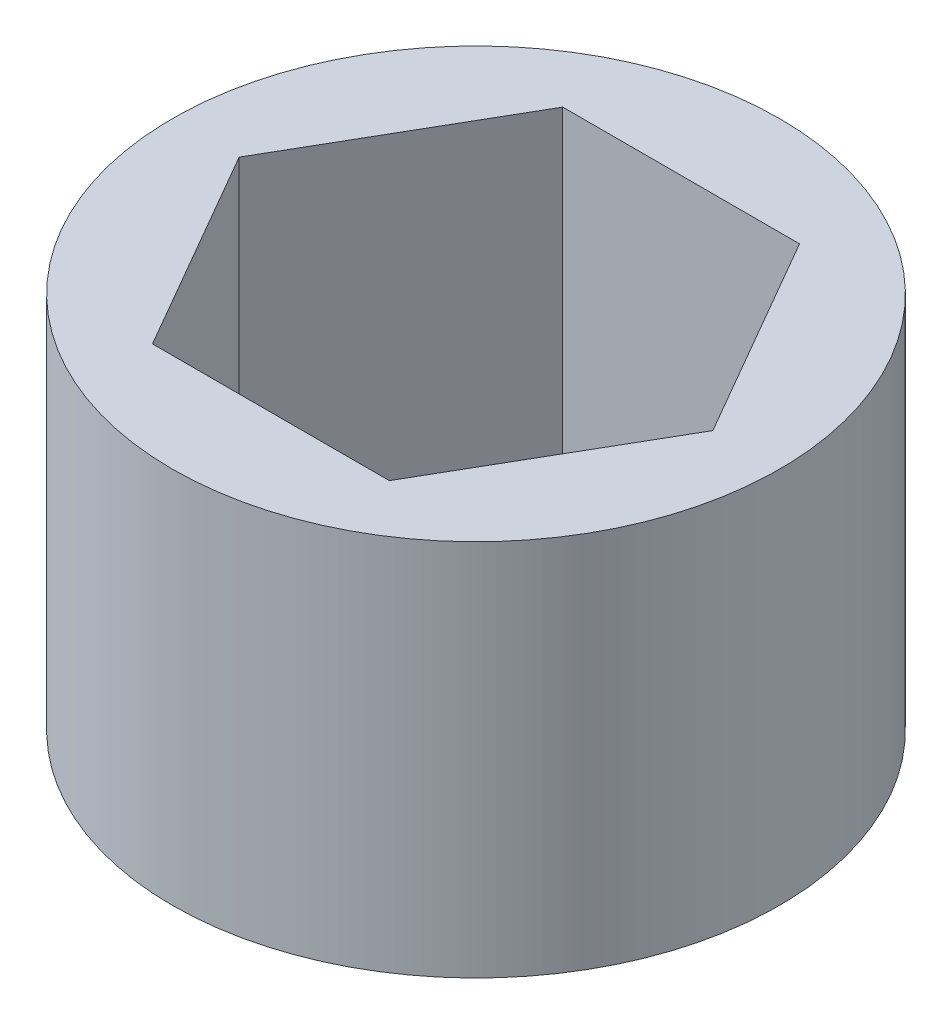
SolidWorks part; units mm, degrees
ref_plane "Front Plane" through (0, 0, 0) normal (0, 0, 1) x (1, 0, 0)
ref_plane "Top Plane" through (0, 0, 0) normal (0, 1, 0) x (1, 0, 0)
ref_plane "Right Plane" through (0, 0, 0) normal (1, 0, 0) x (0, 0, -1)
sketch "Sketch1" plane through (0, 0, 0) normal (0, 1, 0) x (1, 0, 0)
  line L1 (2.7863, -4.826) -> (5.5726, 0)
  line L2 (5.5726, 0) -> (2.7863, 4.826)
  line L3 (2.7863, 4.826) -> (-2.7863, 4.826)
  line L4 (-2.7863, 4.826) -> (-5.5726, 0)
  line L5 (-5.5726, 0) -> (-2.7863, -4.826)
  line L6 (-2.7863, -4.826) -> (2.7863, -4.826)
  circle A0 centre (0, 0) radius 7.1438
  circle A1 centre (0, 0) radius 4.826 construction
  dimension "D1" = 9.652
  dimension "D2" = 14.2875
extrude "Boss-Extrude1" add sketch "Sketch1" along normal mid plane 8.89
